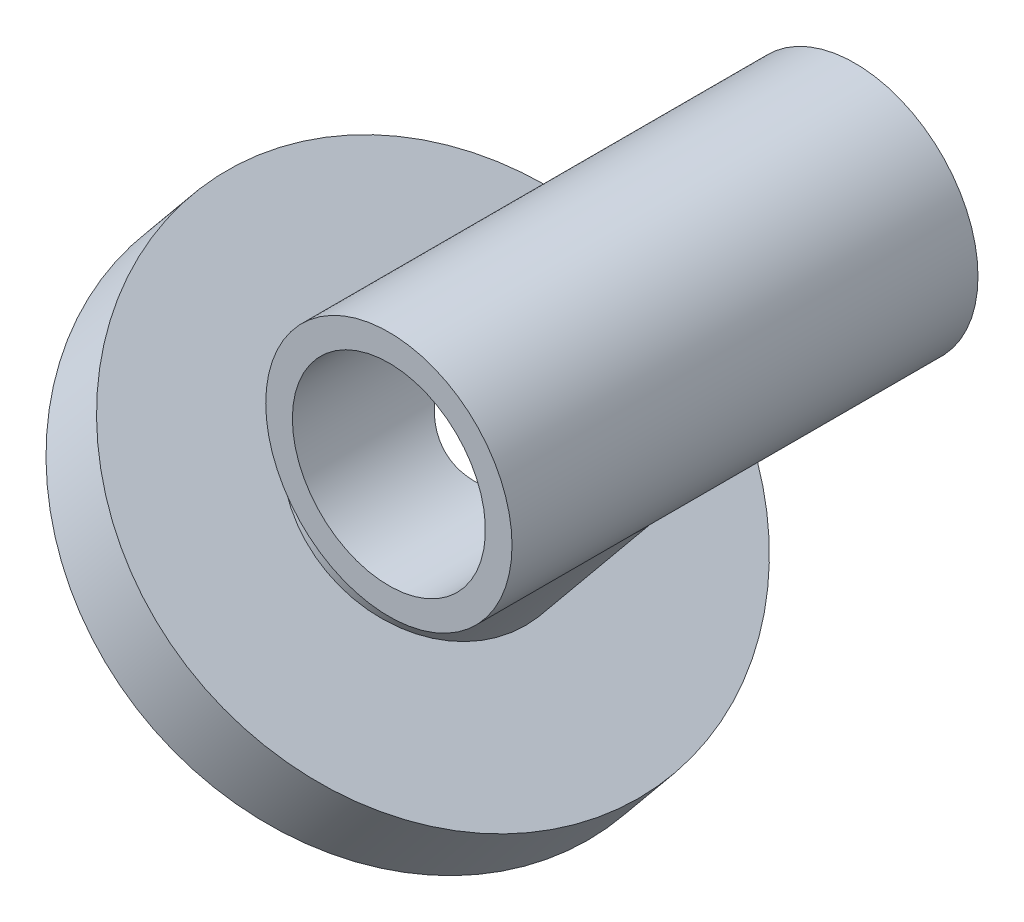
SolidWorks part; units mm, degrees
ref_plane "Plan de face" through (0, 0, 0) normal (0, 0, 1) x (1, 0, 0)
ref_plane "Plan de dessus" through (0, 0, 0) normal (0, 1, 0) x (1, 0, 0)
ref_plane "Plan de droite" through (0, 0, 0) normal (1, 0, 0) x (0, 0, -1)
sketch "Esquisse1" plane through (0, 0, 0) normal (0, 1, 0) x (1, 0, 0)
  line L0 (0, 65.5067) -> (0, -92.2441) construction
  line L1 (7.25, 51.4696) -> (7.25, 16.4696)
  line L2 (7.25, 16.4696) -> (9.25, 16.4696)
  line L3 (9.25, 16.4696) -> (9.25, 51.4696)
  line L4 (9.25, 51.4696) -> (7.25, 51.4696)
  dimension "D1" = 2
  dimension "D2" = 35
  dimension "D3" = 18.5
revolve "Révolution1" add sketch "Esquisse1" angle 360 about L0
hole_wizard "Trou de passage d'axe 3/321" positions "Esquisse3D1" profile "Esquisse2" hole size "3/32" standard "PCS"
sketch3d "Esquisse3D1"
  point P0 (-5.8765, -7.1435, -30.4696)
  dimension "D1" = 14
sketch "Esquisse2" plane through (-5.8765, -7.1435, -30.4696) normal (0, 0, 1) x (0.7723, -0.6353, 0)
  line L0 (0, 0) -> (0, 2)
  line L1 (0, 2) -> (5, 2)
  line L2 (5, 2) -> (5, 0)
  line L5 (5, 0) -> (0, 0)
  line L11 (0, -6.35) -> (0, 107.95) construction
  dimension "Diamètre du perçage jusqu'au prochain" = 10
  dimension "Profondeur du perçage jusqu'au prochain" = 2
ref_plane "Plan2" through (-3.8613, 3.1765, 0) normal (0.7723, -0.6353, 0) x (0, 0, -1)
ref_plane "Plan3" through (0, 0, 0) normal (0.7723, -0.6353, 0) x (0, 0, -1)
sketch "Esquisse6" plane through (0, 0, 0) normal (0.7723, -0.6353, 0) x (0, 0, -1)
  line L0 (30.4696, -20.672) -> (30.4696, 6.3306) construction
  line L1 (22.4696, -16.2201) -> (22.4696, -17.8264)
  line L2 (22.4696, -16.2201) -> (22.4696, -3.2201)
  line L3 (22.4696, -3.2201) -> (21.4696, -3.2201)
  line L4 (21.4696, -3.2201) -> (21.4696, -16.2201)
  line L5 (22.4696, -17.8264) -> (11.4696, -17.8264)
  line L6 (11.4696, -17.8264) -> (11.4696, -22.8029)
  line L7 (21.4696, -16.2201) -> (21.4696, -16.8264)
  line L8 (21.4696, -16.8264) -> (10.4696, -16.8264)
  line L9 (10.4696, -16.8264) -> (10.4696, -22.8029)
  line L10 (10.4696, -22.8029) -> (11.4696, -22.8029)
  line L11 (16.4696, 9.25) -> (16.4696, -9.25) construction
  dimension "D1" = 1
  dimension "D2" = 18
  dimension "D3" = 1
  dimension "D4" = 1
  dimension "D5" = 40
  dimension "D6" = 14
revolve "Révolution2" add sketch "Esquisse6" angle 360 about L0
sketch "Esquisse7" plane through (0, 0, 0) normal (0.7723, -0.6353, 0) x (0, 0, -1)
hole_wizard "Trou de passage d'axe 3/322" positions "Esquisse3D2" profile "Esquisse12" hole size "3/32" standard "PCS" end condition through all
sketch3d "Esquisse3D2"
  circle A0 centre (0, 0, -51.4696) radius 7.25 construction
  point P0 (0, 0, -39.4696)
  point P3 (0, 0, 0)
  point P6 (0, 0, -58.7196)
sketch "Esquisse12" plane through (0, 0, -39.4696) normal (1, 0, 0) x (0, 1, 0)
  line L0 (0, 0) -> (0, 29)
  line L1 (0, 29) -> (7.25, 29)
  line L2 (7.25, 29) -> (7.25, 0)
  line L5 (7.25, 0) -> (0, 0)
  line L11 (0, -6.35) -> (0, 107.95) construction
  dimension "Diamètre du perçage jusqu'au prochain" = 14.5
  dimension "Profondeur du perçage jusqu'au prochain" = 29
